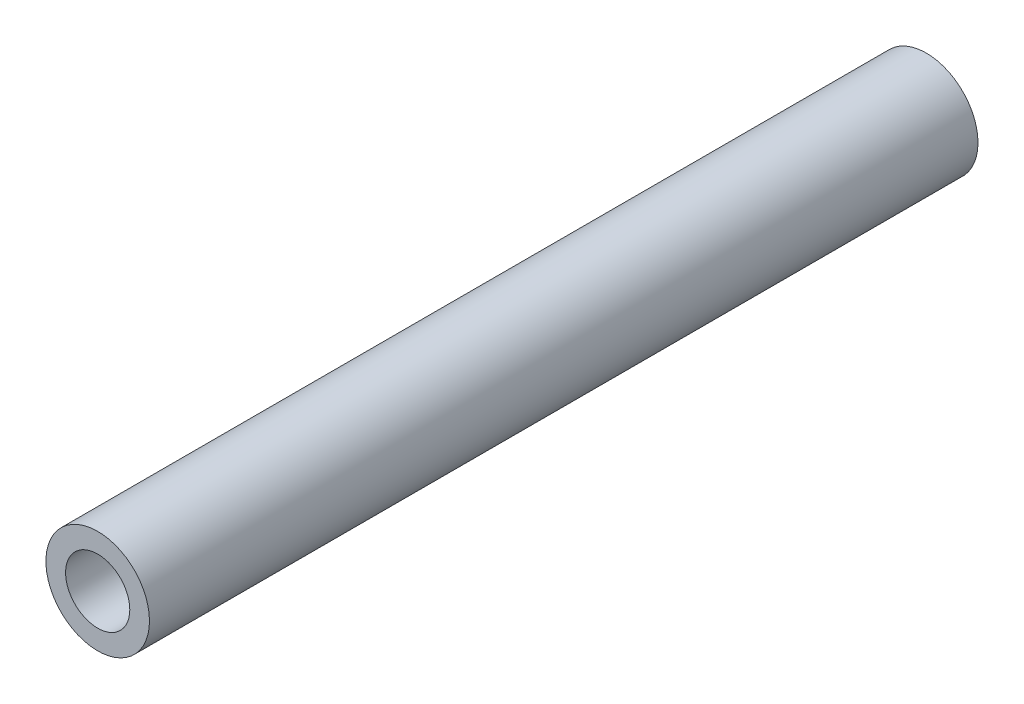
SolidWorks part; units mm, degrees
material "7050-T73510"
ref_plane "前视基准面" through (0, 0, 0) normal (0, 0, 1) x (1, 0, 0)
ref_plane "上视基准面" through (0, 0, 0) normal (0, 1, 0) x (1, 0, 0)
ref_plane "右视基准面" through (0, 0, 0) normal (1, 0, 0) x (0, 0, -1)
sketch "草图1" plane through (0, 0, 0) normal (0, 0, 1) x (1, 0, 0)
  circle A0 centre (0, 0) radius 2.5
  circle A1 centre (0, 0) radius 1.55
  dimension "D1" = 3.1
  dimension "D2" = 5
extrude "凸台-拉伸1" add sketch "草图1" along normal blind 40
